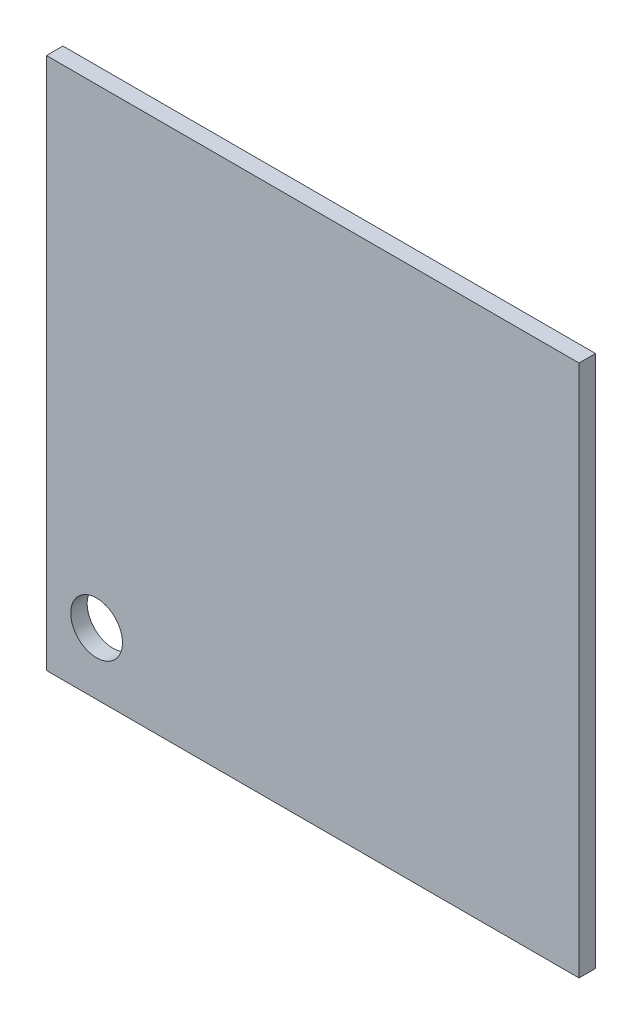
SolidWorks part; units mm, degrees
ref_plane "Front Plane" through (0, 0, 0) normal (1, 0, 0) x (0, 1, 0)
ref_plane "Top Plane" through (0, 0, 0) normal (0, 0, 1) x (0, 1, 0)
ref_plane "Right Plane" through (0, 0, 0) normal (0, 1, 0) x (-1, 0, 0)
sketch "Sketch1" plane through (0, 0, 0) normal (0, 0, 1) x (0, 1, 0)
  line L1 (-48.5, 48.5) -> (48.5, 48.5)
  line L2 (-48.5, 48.5) -> (-48.5, -48.5)
  line L3 (-48.5, -48.5) -> (48.5, -48.5)
  line L4 (48.5, 48.5) -> (48.5, -48.5)
  line L5 (-48.5, 48.5) -> (48.5, -48.5) construction
  line L6 (-48.5, -48.5) -> (48.5, 48.5) construction
  point P0 (0, 0)
  dimension "D1" = 97
  dimension "D2" = 97
extrude "Boss-Extrude1" add sketch "Sketch1" along normal blind 3
sketch "Sketch2" plane through (0, 0, 3) normal (0, 0, 1) x (0, -1, 0)
  circle A0 centre (37.2184, -39.3677) radius 4.7143
extrude "Cut-Extrude1" cut sketch "Sketch2" against normal blind 10
